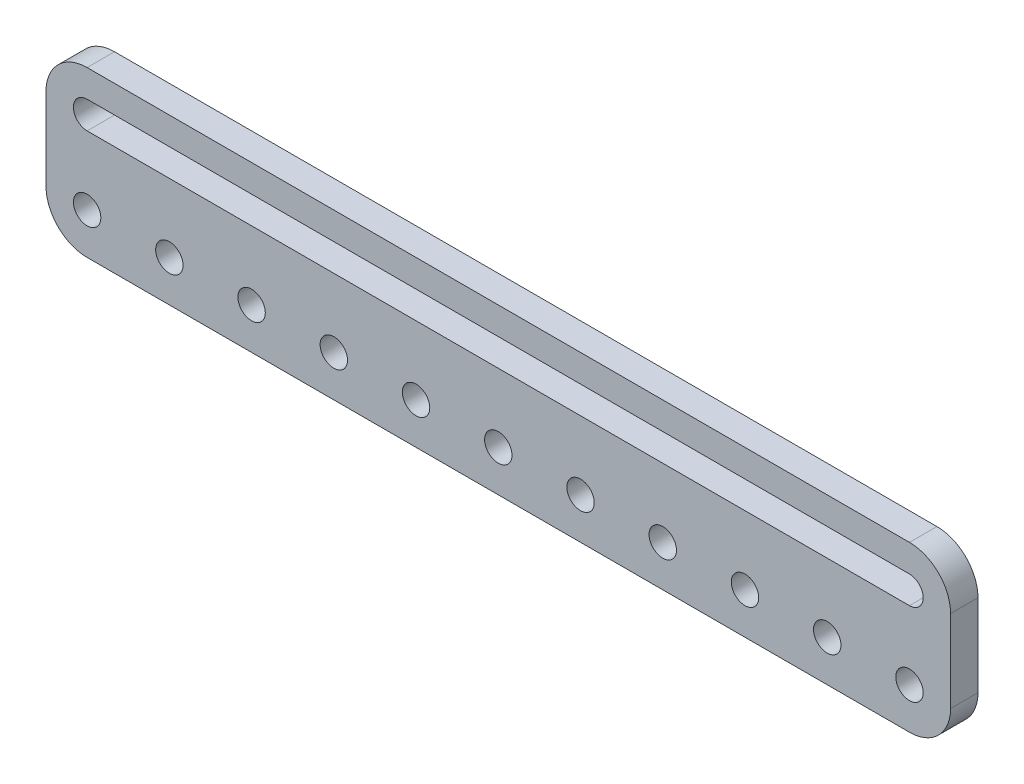
SolidWorks part; units mm, degrees
ref_plane "Alzado" through (0, 0, 0) normal (0, 0, 1) x (1, 0, 0)
ref_plane "Planta" through (0, 0, 0) normal (0, 1, 0) x (1, 0, 0)
ref_plane "Vista lateral" through (0, 0, 0) normal (1, 0, 0) x (0, 0, -1)
sketch "Model" plane through (0, 0, 0) normal (0, 0, 1) x (1, 0, 0)
  line L0 (256.4291, 228.7422) -> (346.4291, 228.7422)
  line L1 (346.4291, 210.7422) -> (256.4291, 210.7422)
  line L2 (350.9291, 224.2422) -> (350.9291, 215.2422)
  line L3 (251.9291, 224.2422) -> (251.9291, 215.2422)
  line L4 (256.4291, 225.7422) -> (346.4291, 225.7422)
  line L5 (256.4291, 222.7422) -> (346.4291, 222.7422)
  arc A0 (350.9291, 224.2422) -> (346.4291, 228.7422) centre (346.4291, 224.2422) ccw
  arc A1 (256.4291, 228.7422) -> (251.9291, 224.2422) centre (256.4291, 224.2422) ccw
  arc A2 (251.9291, 215.2422) -> (256.4291, 210.7422) centre (256.4291, 215.2422) ccw
  arc A3 (346.4291, 210.7422) -> (350.9291, 215.2422) centre (346.4291, 215.2422) ccw
  circle A4 centre (337.4291, 215.2422) radius 1.5
  circle A5 centre (319.4291, 215.2422) radius 1.5
  circle A6 centre (328.4291, 215.2422) radius 1.5
  circle A7 centre (310.4291, 215.2422) radius 1.5
  circle A8 centre (292.4291, 215.2422) radius 1.5
  circle A9 centre (301.4291, 215.2422) radius 1.5
  circle A10 centre (274.4291, 215.2422) radius 1.5
  circle A11 centre (283.4291, 215.2422) radius 1.5
  circle A12 centre (265.4291, 215.2422) radius 1.5
  circle A13 centre (256.4291, 215.2422) radius 1.5
  circle A14 centre (346.4291, 215.2422) radius 1.5
  arc A15 (256.4291, 225.7422) -> (256.4291, 222.7422) centre (256.4291, 224.2422) ccw
  arc A16 (346.4291, 222.7422) -> (346.4291, 225.7422) centre (346.4291, 224.2422) ccw
extrude "Saliente-Extruir1" add sketch "Model" along normal blind 3
